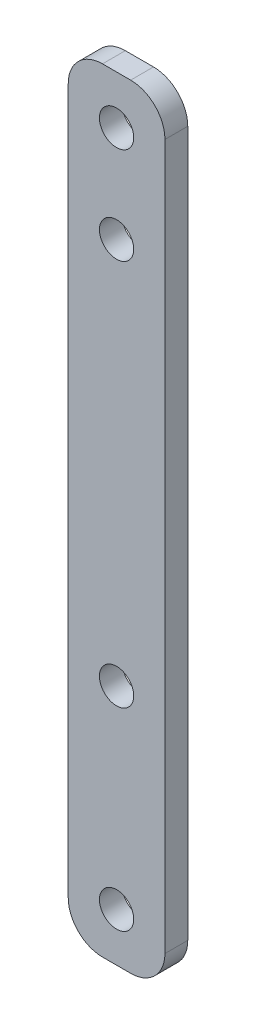
SolidWorks part; units mm, degrees
ref_plane "Front Plane" through (0, 0, 0) normal (0, 0, 1) x (1, 0, 0)
ref_plane "Top Plane" through (0, 0, 0) normal (0, 1, 0) x (1, 0, 0)
ref_plane "Right Plane" through (0, 0, 0) normal (1, 0, 0) x (0, 0, -1)
sketch "Sketch1" plane through (0, 0, 0) normal (0, 0, 1) x (1, 0, 0)
  line L1 (0, 0) -> (12.7, 0)
  line L2 (0, 0) -> (0, 101.6)
  line L3 (0, 101.6) -> (12.7, 101.6)
  line L4 (12.7, 0) -> (12.7, 101.6)
  circle A0 centre (6.35, 6.35) radius 2.25
  circle A2 centre (6.35, 95.25) radius 2.25
  circle A3 centre (6.35, 82.55) radius 2.25
  circle A6 centre (6.35, 31.75) radius 2.25
  point P13 (0, 0)
  point P15 (-2.0308, 30.3734)
  dimension "D3" = 4.5
  dimension "D1" = 101.6
  dimension "D2" = 12.7
  dimension "D4" = 6.35
  dimension "D5" = 6.35
  dimension "D6" = 25.4
  dimension "D7" = 88.9
  dimension "D8" = 12.7
extrude "Boss-Extrude1" add sketch "Sketch1" along normal blind 3
fillet "Fillet1" radius 4.5 4 edges at (12.7, 0, 1.5) (0, 0, 1.5) (12.7, 101.6, 1.5) (0, 101.6, 1.5)
